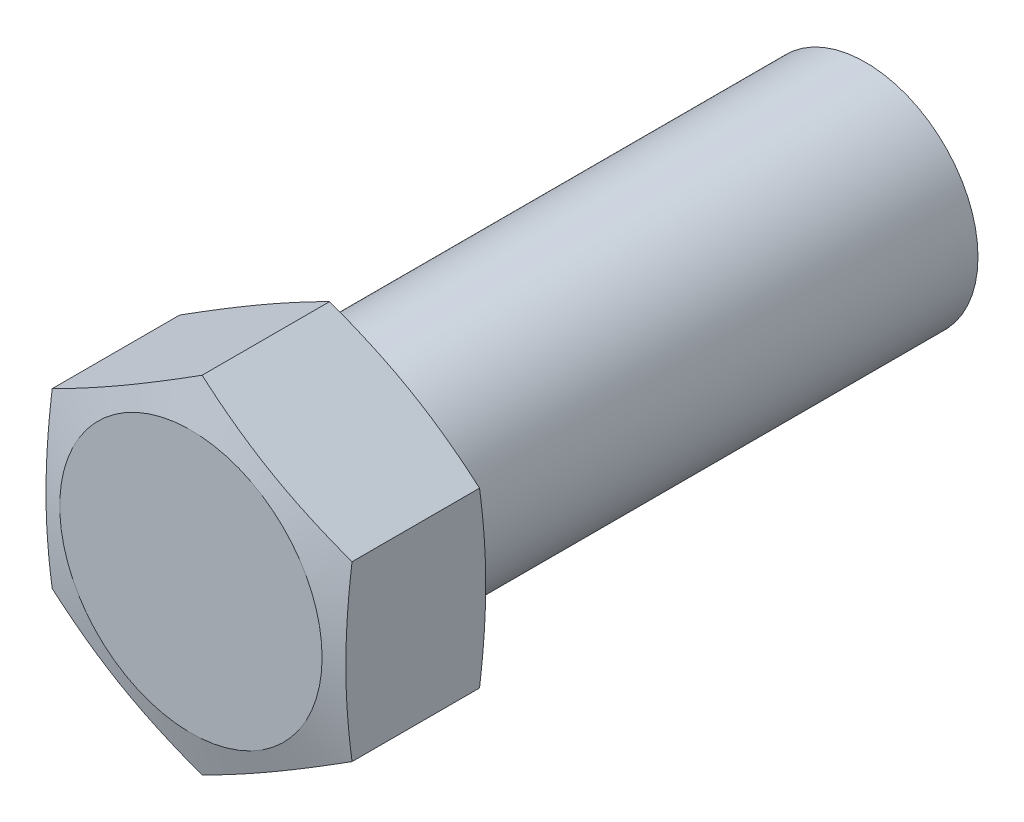
SolidWorks part; units mm, degrees
ref_plane "Plano frontal" through (0, 0, 0) normal (0, 0, 1) x (1, 0, 0)
ref_plane "Plano superior" through (0, 0, 0) normal (0, 1, 0) x (1, 0, 0)
ref_plane "Plano direito" through (0, 0, 0) normal (1, 0, 0) x (0, 0, -1)
sketch "Esboço1" plane through (0, 0, 0) normal (0, 0, 1) x (1, 0, 0)
  line L1 (0, -4.6188) -> (4, -2.3094)
  line L2 (4, -2.3094) -> (4, 2.3094)
  line L3 (4, 2.3094) -> (0, 4.6188)
  line L4 (0, 4.6188) -> (-4, 2.3094)
  line L5 (-4, 2.3094) -> (-4, -2.3094)
  line L6 (-4, -2.3094) -> (0, -4.6188)
  circle A0 centre (0, 0) radius 4 construction
  dimension "D1" = 8
extrude "Ressalto-extrusão1" add sketch "Esboço1" along normal blind 4
sketch "Esboço2" plane through (0, 0, 4) normal (0, 0, 1) x (1, 0, 0)
  circle A0 centre (0, 0) radius 3.5
extrude "Corte-extrusão1" cut sketch "Esboço2" against normal blind 15 draft 75 flip side to cut
sketch "Esboço3" plane through (0, 0, 0) normal (0, 0, -1) x (-1, 0, 0)
  circle A0 centre (0, 0) radius 3.5
extrude "Corte-extrusão5" cut sketch "Esboço3" against normal blind 15 draft 75 flip side to cut
sketch "Esboço9" plane through (0, 0, 0) normal (0, 0, -1) x (-1, 0, 0)
  circle A0 centre (0, 0) radius 3
  dimension "D1" = 6
extrude "Ressalto-extrusão2" add sketch "Esboço9" along normal blind 14
cosmetic thread "Representação de rosca1" parameters "D2"=5
